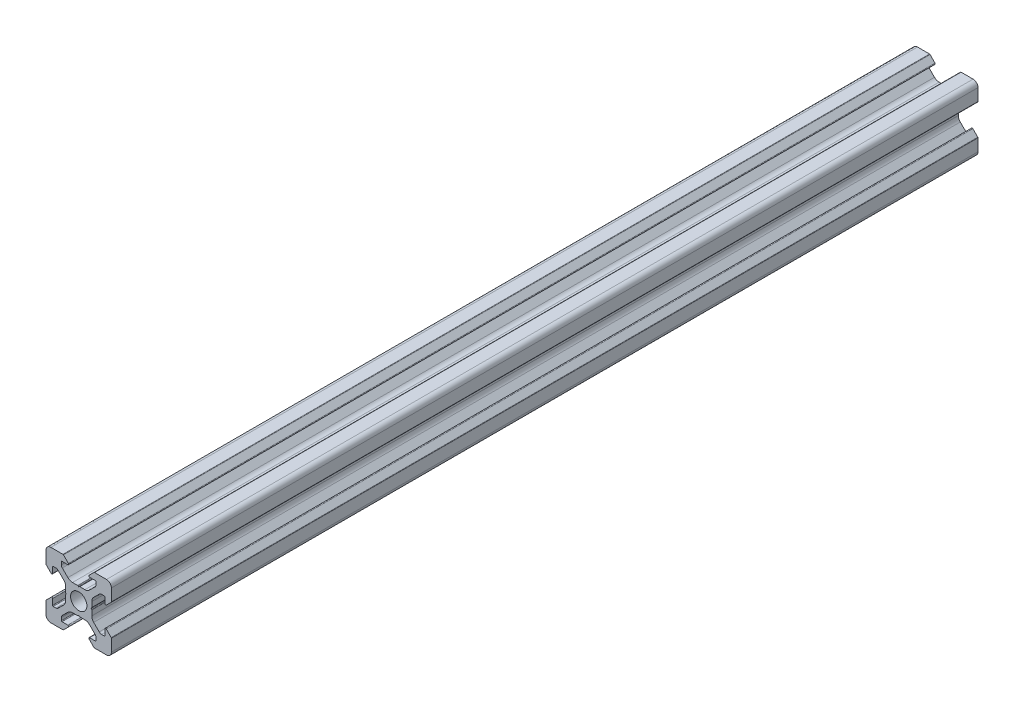
SolidWorks part; units mm, degrees
ref_plane "Спереди" through (0, 0, 0) normal (0, 0, 1) x (1, 0, 0)
ref_plane "Сверху" through (0, 0, 0) normal (0, 1, 0) x (1, 0, 0)
ref_plane "Справа" through (0, 0, 0) normal (1, 0, 0) x (0, 0, -1)
sketch "Model" plane through (0, 0, 0) normal (0, 0, 1) x (1, 0, 0)
  line L0 (18.9421, 33.3622) -> (18.9421, 34.9233)
  line L1 (18.3564, 36.3375) -> (16.6623, 38.0316)
  line L2 (15.9551, 38.3245) -> (15.1421, 38.3245)
  line L3 (14.9421, 38.1245) -> (14.9421, 36.3545)
  line L4 (13.0154, 37.6777) -> (14.5154, 36.1777)
  line L5 (12.9421, 37.8545) -> (12.9421, 41.5245)
  line L6 (18.2889, 42.9513) -> (19.7889, 41.4513)
  line L7 (22.7606, 36.9697) -> (22.9421, 36.8245)
  line L8 (23.1237, 36.9697) -> (22.9421, 36.8245)
  line L9 (23.2798, 37.0245) -> (24.8409, 37.0245)
  line L10 (26.2551, 37.6103) -> (27.9493, 39.3044)
  line L11 (28.2421, 40.0115) -> (28.2421, 40.8245)
  line L12 (28.0421, 41.0245) -> (26.2721, 41.0245)
  line L13 (27.5954, 42.9513) -> (26.0954, 41.4513)
  line L14 (27.7721, 43.0245) -> (31.4421, 43.0245)
  line L15 (32.9421, 37.8545) -> (32.9421, 41.5245)
  line L16 (32.8689, 37.6777) -> (31.3689, 36.1777)
  line L17 (30.9421, 38.1245) -> (30.9421, 36.3545)
  line L18 (29.9292, 38.3245) -> (30.7421, 38.3245)
  line L19 (27.5279, 36.3375) -> (29.222, 38.0316)
  line L20 (26.9421, 33.3622) -> (26.9421, 34.9233)
  line L21 (26.8874, 33.206) -> (26.7421, 33.0245)
  line L22 (26.8874, 32.843) -> (26.7421, 33.0245)
  line L23 (26.9421, 32.6868) -> (26.9421, 31.1257)
  line L24 (27.5279, 29.7115) -> (29.222, 28.0174)
  line L25 (29.9292, 27.7245) -> (30.7421, 27.7245)
  line L26 (30.9421, 27.9245) -> (30.9421, 29.6945)
  line L27 (32.8689, 28.3713) -> (31.3689, 29.8713)
  line L28 (32.9421, 28.1945) -> (32.9421, 24.5245)
  line L29 (27.7721, 23.0245) -> (31.4421, 23.0245)
  line L30 (27.5954, 23.0977) -> (26.0954, 24.5977)
  line L31 (28.0421, 25.0245) -> (26.2721, 25.0245)
  line L32 (28.2421, 26.0375) -> (28.2421, 25.2245)
  line L33 (26.2551, 28.4387) -> (27.9493, 26.7446)
  line L34 (23.2798, 29.0245) -> (24.8409, 29.0245)
  line L35 (23.1237, 29.0793) -> (22.9421, 29.2245)
  line L36 (22.7606, 29.0793) -> (22.9421, 29.2245)
  line L37 (19.6292, 28.4387) -> (17.935, 26.7446)
  line L38 (17.6421, 26.0375) -> (17.6421, 25.2245)
  line L39 (17.8421, 25.0245) -> (19.6121, 25.0245)
  line L40 (18.2889, 23.0977) -> (19.7889, 24.5977)
  line L41 (18.1121, 23.0245) -> (14.4421, 23.0245)
  line L42 (12.9421, 28.1945) -> (12.9421, 24.5245)
  line L43 (13.0154, 28.3713) -> (14.5154, 29.8713)
  line L44 (14.9421, 27.9245) -> (14.9421, 29.6945)
  line L45 (15.9551, 27.7245) -> (15.1421, 27.7245)
  line L46 (18.3564, 29.7115) -> (16.6623, 28.0174)
  line L47 (18.9421, 32.6868) -> (18.9421, 31.1257)
  line L48 (18.9969, 32.843) -> (19.1421, 33.0245)
  line L49 (18.9969, 33.206) -> (19.1421, 33.0245)
  line L50 (22.6045, 29.0245) -> (21.0434, 29.0245)
  line L51 (22.6045, 37.0245) -> (21.0434, 37.0245)
  line L52 (19.6292, 37.6103) -> (17.935, 39.3044)
  line L53 (17.6421, 40.0115) -> (17.6421, 40.8245)
  line L54 (17.8421, 41.0245) -> (19.6121, 41.0245)
  line L55 (18.1121, 43.0245) -> (14.4421, 43.0245)
  arc A0 (18.9421, 33.3622) -> (18.9969, 33.206) centre (19.1921, 33.3622) ccw
  arc A1 (18.9421, 34.9233) -> (18.3564, 36.3375) centre (16.9421, 34.9233) ccw
  arc A2 (16.6623, 38.0316) -> (15.9551, 38.3245) centre (15.9551, 37.3245) ccw
  arc A3 (15.1421, 38.3245) -> (14.9421, 38.1245) centre (15.1421, 38.1245) ccw
  arc A4 (14.5154, 36.1777) -> (14.9421, 36.3545) centre (14.6921, 36.3545) ccw
  arc A5 (12.9421, 37.8545) -> (13.0154, 37.6777) centre (13.1921, 37.8545) ccw
  arc A6 (14.4421, 43.0245) -> (12.9421, 41.5245) centre (14.4421, 41.5245) ccw
  arc A7 (18.2889, 42.9513) -> (18.1121, 43.0245) centre (18.1121, 42.7745) ccw
  arc A8 (19.6121, 41.0245) -> (19.7889, 41.4513) centre (19.6121, 41.2745) ccw
  arc A9 (17.8421, 41.0245) -> (17.6421, 40.8245) centre (17.8421, 40.8245) ccw
  arc A10 (17.6421, 40.0115) -> (17.935, 39.3044) centre (18.6421, 40.0115) ccw
  arc A11 (19.6292, 37.6103) -> (21.0434, 37.0245) centre (21.0434, 39.0245) ccw
  arc A12 (22.7606, 36.9697) -> (22.6045, 37.0245) centre (22.6045, 36.7745) ccw
  arc A13 (23.2798, 37.0245) -> (23.1237, 36.9697) centre (23.2798, 36.7745) ccw
  arc A14 (24.8409, 37.0245) -> (26.2551, 37.6103) centre (24.8409, 39.0245) ccw
  arc A15 (27.9493, 39.3044) -> (28.2421, 40.0115) centre (27.2421, 40.0115) ccw
  arc A16 (28.2421, 40.8245) -> (28.0421, 41.0245) centre (28.0421, 40.8245) ccw
  arc A17 (26.0954, 41.4513) -> (26.2721, 41.0245) centre (26.2721, 41.2745) ccw
  arc A18 (27.7721, 43.0245) -> (27.5954, 42.9513) centre (27.7721, 42.7745) ccw
  arc A19 (32.9421, 41.5245) -> (31.4421, 43.0245) centre (31.4421, 41.5245) ccw
  arc A20 (32.8689, 37.6777) -> (32.9421, 37.8545) centre (32.6921, 37.8545) ccw
  arc A21 (30.9421, 36.3545) -> (31.3689, 36.1777) centre (31.1921, 36.3545) ccw
  arc A22 (30.9421, 38.1245) -> (30.7421, 38.3245) centre (30.7421, 38.1245) ccw
  arc A23 (29.9292, 38.3245) -> (29.222, 38.0316) centre (29.9292, 37.3245) ccw
  arc A24 (27.5279, 36.3375) -> (26.9421, 34.9233) centre (28.9421, 34.9233) ccw
  arc A25 (26.8874, 33.206) -> (26.9421, 33.3622) centre (26.6921, 33.3622) ccw
  arc A26 (26.9421, 32.6868) -> (26.8874, 32.843) centre (26.6921, 32.6868) ccw
  arc A27 (26.9421, 31.1257) -> (27.5279, 29.7115) centre (28.9421, 31.1257) ccw
  arc A28 (29.222, 28.0174) -> (29.9292, 27.7245) centre (29.9292, 28.7245) ccw
  arc A29 (30.7421, 27.7245) -> (30.9421, 27.9245) centre (30.7421, 27.9245) ccw
  arc A30 (31.3689, 29.8713) -> (30.9421, 29.6945) centre (31.1921, 29.6945) ccw
  arc A31 (32.9421, 28.1945) -> (32.8689, 28.3713) centre (32.6921, 28.1945) ccw
  arc A32 (31.4421, 23.0245) -> (32.9421, 24.5245) centre (31.4421, 24.5245) ccw
  arc A33 (27.5954, 23.0977) -> (27.7721, 23.0245) centre (27.7721, 23.2745) ccw
  arc A34 (26.2721, 25.0245) -> (26.0954, 24.5977) centre (26.2721, 24.7745) ccw
  arc A35 (28.0421, 25.0245) -> (28.2421, 25.2245) centre (28.0421, 25.2245) ccw
  arc A36 (28.2421, 26.0375) -> (27.9493, 26.7446) centre (27.2421, 26.0375) ccw
  arc A37 (26.2551, 28.4387) -> (24.8409, 29.0245) centre (24.8409, 27.0245) ccw
  arc A38 (23.1237, 29.0793) -> (23.2798, 29.0245) centre (23.2798, 29.2745) ccw
  arc A39 (22.6045, 29.0245) -> (22.7606, 29.0793) centre (22.6045, 29.2745) ccw
  arc A40 (21.0434, 29.0245) -> (19.6292, 28.4387) centre (21.0434, 27.0245) ccw
  arc A41 (17.935, 26.7446) -> (17.6421, 26.0375) centre (18.6421, 26.0375) ccw
  arc A42 (17.6421, 25.2245) -> (17.8421, 25.0245) centre (17.8421, 25.2245) ccw
  arc A43 (19.7889, 24.5977) -> (19.6121, 25.0245) centre (19.6121, 24.7745) ccw
  arc A44 (18.1121, 23.0245) -> (18.2889, 23.0977) centre (18.1121, 23.2745) ccw
  arc A45 (12.9421, 24.5245) -> (14.4421, 23.0245) centre (14.4421, 24.5245) ccw
  arc A46 (13.0154, 28.3713) -> (12.9421, 28.1945) centre (13.1921, 28.1945) ccw
  arc A47 (14.9421, 29.6945) -> (14.5154, 29.8713) centre (14.6921, 29.6945) ccw
  arc A48 (14.9421, 27.9245) -> (15.1421, 27.7245) centre (15.1421, 27.9245) ccw
  arc A49 (15.9551, 27.7245) -> (16.6623, 28.0174) centre (15.9551, 28.7245) ccw
  arc A50 (18.3564, 29.7115) -> (18.9421, 31.1257) centre (16.9421, 31.1257) ccw
  arc A51 (18.9969, 32.843) -> (18.9421, 32.6868) centre (19.1921, 32.6868) ccw
  circle A52 centre (22.9421, 33.0245) radius 2.5
extrude "Бобышка-Вытянуть1" add sketch "Model" along normal blind 265
